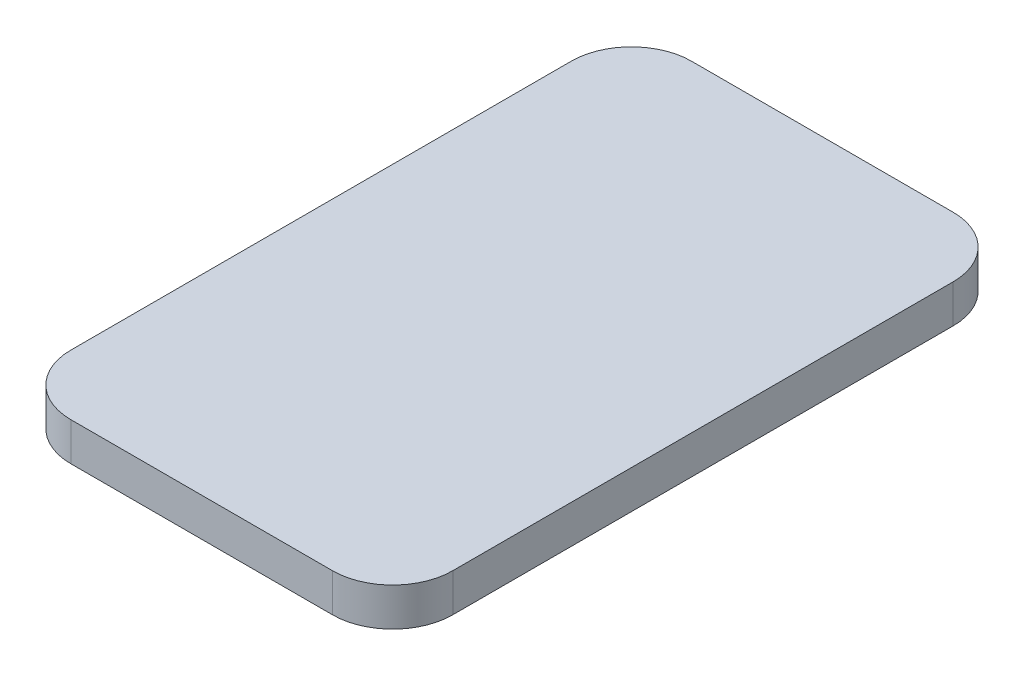
SolidWorks part; units mm, degrees
material "1.0037 (S235JR)"
ref_plane "E_Rechts" through (0, 0, 0) normal (0, 0, 1) x (1, 0, 0)
ref_plane "E_Vorne" through (0, 0, 0) normal (0, 1, 0) x (1, 0, 0)
ref_plane "E_Oben" through (0, 0, 0) normal (1, 0, 0) x (0, 0, -1)
sketch "Skizze1" plane through (0, 0, 0) normal (0, 1, 0) x (1, 0, 0)
  line L4 (-27.4, -65) -> (27.4, -65)
  line L5 (-40, -52.4) -> (-40, 52.4)
  line L6 (27.4, 65) -> (-27.4, 65)
  line L7 (40, 52.4) -> (40, -52.4)
  line L8 (0, -55) -> (0, 55) construction
  line L9 (-55, 0) -> (55, 0) construction
  arc A0 (40, 52.4) -> (27.4, 65) centre (27.4, 52.4) ccw
  arc A1 (27.4, -65) -> (40, -52.4) centre (27.4, -52.4) ccw
  arc A2 (-40, -52.4) -> (-27.4, -65) centre (-27.4, -52.4) ccw
  arc A3 (-27.4, 65) -> (-40, 52.4) centre (-27.4, 52.4) ccw
  dimension "D1" = 12.6
  dimension "D3" = 130
  dimension "D4" = 80
  dimension "D5" = 40
  dimension "D6" = 65
extrude "Aufsatz-Linear austragen1" add sketch "Skizze1" along normal blind 8
